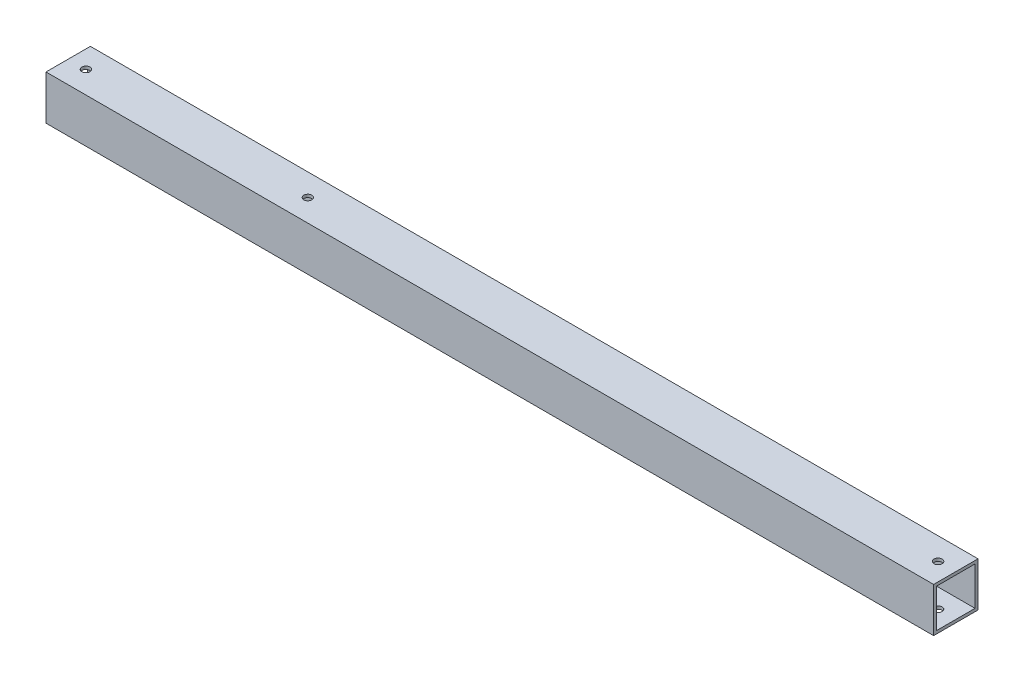
SolidWorks part; units mm, degrees
ref_plane "Front Plane" through (0, 0, 0) normal (0, 0, 1) x (1, 0, 0)
ref_plane "Top Plane" through (0, 0, 0) normal (0, 1, 0) x (1, 0, 0)
ref_plane "Right Plane" through (0, 0, 0) normal (1, 0, 0) x (0, 0, -1)
sketch "Sketch1" plane through (0, 0, 0) normal (1, 0, 0) x (0, 0, -1)
  line L1 (15, 15) -> (-15, 15)
  line L2 (15, 15) -> (15, -15)
  line L3 (15, -15) -> (-15, -15)
  line L4 (-15, 15) -> (-15, -15)
  line L5 (15, 15) -> (-15, -15) construction
  line L6 (15, -15) -> (-15, 15) construction
  line L7 (-13, 13) -> (13, 13)
  line L8 (-13, 13) -> (-13, -13)
  line L9 (-13, -13) -> (13, -13)
  line L10 (13, 13) -> (13, -13)
  line L11 (-13, 13) -> (13, -13) construction
  line L12 (-13, -13) -> (13, 13) construction
  point P0 (0, 0)
  point P5 (0, 0)
  dimension "D1" = 30
  dimension "D2" = 30
  dimension "D3" = 2
extrude "Boss-Extrude1" add sketch "Sketch1" along normal mid plane 600
sketch "Sketch2" plane through (0, 0, 0) normal (0, 1, 0) x (1, 0, 0)
  line L0 (300, 15) -> (300, -15) construction
  circle A0 centre (288, 0) radius 2.75
  dimension "D1" = 5.5
  dimension "D2" = 12
extrude "Cut-Extrude1" cut sketch "Sketch2" against normal through all both and the other way through all
mirror "Mirror1" about plane through (0, 0, 0) normal (1, 0, 0) of "Cut-Extrude1"
sketch "Sketch3" plane through (0, 0, 0) normal (0, 1, 0) x (1, 0, 0)
  line L0 (-288, 0) -> (-138, 0) construction
  circle A0 centre (-138, 0) radius 2.75
  dimension "D2" = 5.5
  dimension "D1" = 150
extrude "Cut-Extrude2" cut sketch "Sketch3" against normal through all both and the other way through all
equation "\"D2@Sketch1\"=\"w\""
equation "\"D1@Sketch1\"=\"w\""
equation "\"t\"= 2"
equation "\"w\"= 30"
equation "\"D3@Sketch1\"=\"t\""
